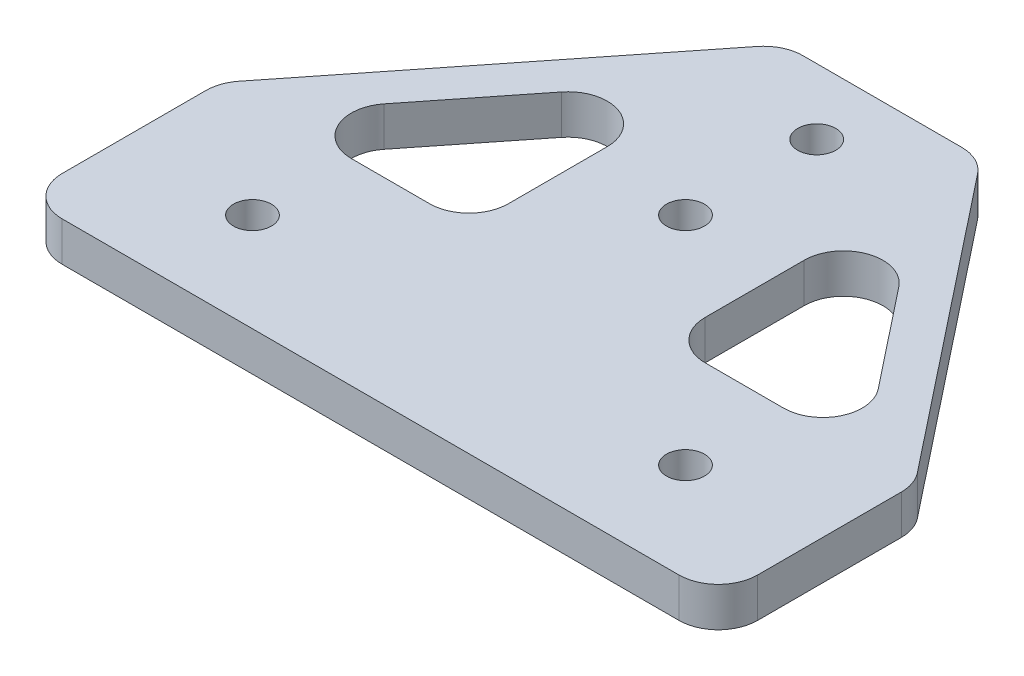
SolidWorks part; units mm, degrees
material "Thornel Mat VMA"
ref_plane "前视基准面" through (0, 0, 0) normal (0, 0, 1) x (1, 0, 0)
ref_plane "上视基准面" through (0, 0, 0) normal (0, 1, 0) x (1, 0, 0)
ref_plane "右视基准面" through (0, 0, 0) normal (1, 0, 0) x (0, 0, -1)
other "Configuration Table"
sketch "草图1" plane through (0, 0, 0) normal (0, 1, 0) x (1, 0, 0)
  line L0 (0, 31.117) -> (0, -29.5669) construction
  line L1 (-26.5, -7.5) -> (26.5, -7.5)
  line L2 (-26.5, -7.5) -> (-26.5, 7.5)
  line L3 (-26.5, 7.5) -> (26.5, 7.5) construction
  line L4 (26.5, -7.5) -> (26.5, 7.5)
  line L5 (-26.5, -7.5) -> (26.5, 7.5) construction
  line L6 (-26.5, 7.5) -> (26.5, -7.5) construction
  line L7 (-7.5, -7.5) -> (7.5, -7.5)
  line L8 (-7.5, -7.5) -> (-7.5, 31.5) construction
  line L9 (-7.5, 31.5) -> (7.5, 31.5)
  line L10 (7.5, -7.5) -> (7.5, 31.5) construction
  line L11 (-41.1018, 0) -> (44.7948, 0) construction
  line L12 (-26.5, 7.5) -> (-7.5, 31.5)
  line L13 (7.5, 31.5) -> (26.5, 7.5)
  line L14 (-7.5, 26.6668) -> (-22.6737, 7.5)
  line L15 (-22.6737, 7.5) -> (-7.5, 7.5)
  line L16 (-7.5, 7.5) -> (-7.5, 26.6668)
  line L17 (7.5, 26.6668) -> (22.6737, 7.5)
  line L18 (22.6737, 7.5) -> (7.5, 7.5)
  line L19 (7.5, 7.5) -> (7.5, 26.6668)
  circle A0 centre (-16.5, 0) radius 1.45
  circle A1 centre (16.5, 0) radius 1.45
  circle A2 centre (0, 16.5) radius 1.45
  circle A3 centre (0, 26.5) radius 1.45
  point P0 (0, 0)
  point P28 (-7.5, 25.2351)
  point P29 (-7.5, 22.5224)
  point P30 (-7.5, 30.9561)
  point P31 (7.5, 27.8305)
  dimension "D3" = 9
  dimension "D5" = 10
  dimension "D6" = 2.9
  dimension "D7" = 9
  dimension "D8" = 10
  dimension "D9" = 5
  dimension "D1" = 15
  dimension "D2" = 15
  dimension "D4" = 9
  dimension "D10" = 3
  dimension "D11" = 3
extrude "凸台-拉伸1" add sketch "草图1" along normal blind 3 contours L13 L9 L12 L2 L1 L4 A3 A2 A1 A0 L16 L15 L14 L18 L19 L17
fillet "圆角2" radius 3 12 edges at (22.6737, 1.5, -7.5) (7.5, 1.5, -26.6668) (26.5, 1.5, 7.5) (-26.5, 1.5, 7.5) (-26.5, 1.5, -7.5) (-7.5, 1.5, -31.5) (7.5, 1.5, -31.5) (-7.5, 1.5, -26.6668) (-22.6737, 1.5, -7.5) (-7.5, 1.5, -7.5) (26.5, 1.5, -7.5) (7.5, 1.5, -7.5)
